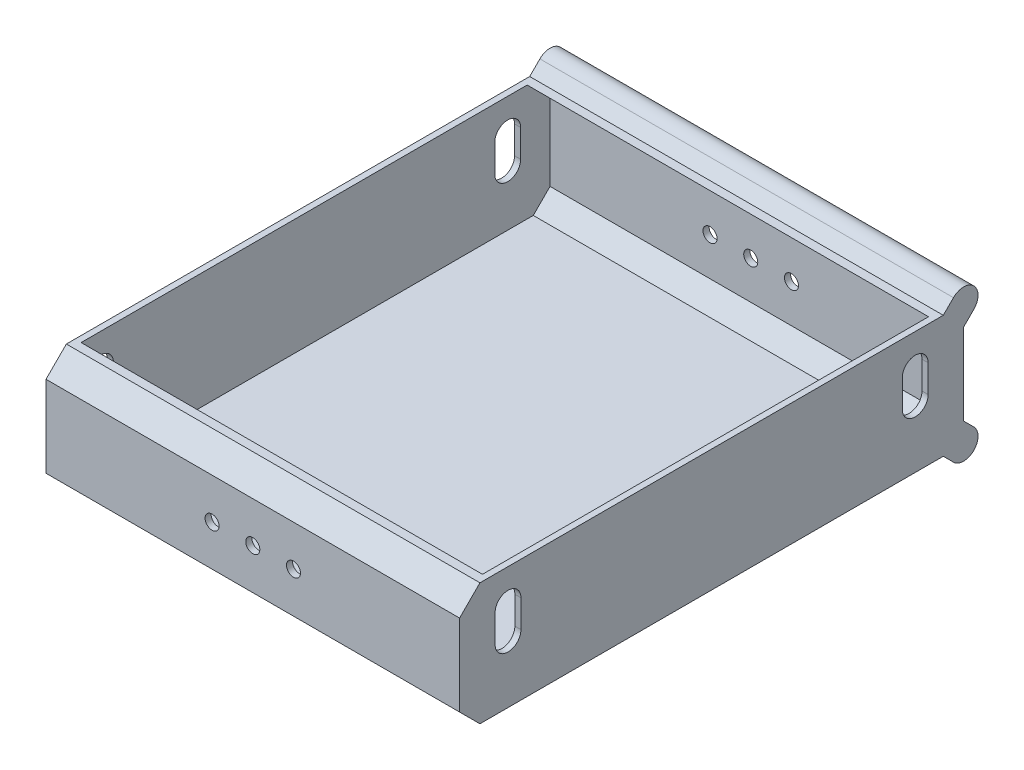
SolidWorks part; units mm, degrees
ref_plane "Front Plane" through (0, 0, 0) normal (0, 0, 1) x (1, 0, 0)
ref_plane "Top Plane" through (0, 0, 0) normal (0, 1, 0) x (1, 0, 0)
ref_plane "Right Plane" through (0, 0, 0) normal (1, 0, 0) x (0, 0, -1)
sketch "Sketch1" plane through (0, 0, 0) normal (0, 1, 0) x (1, 0, 0)
  line L1 (-101.6, 123.825) -> (101.6, 123.825)
  line L2 (-101.6, 123.825) -> (-101.6, -123.825)
  line L3 (-101.6, -123.825) -> (101.6, -123.825)
  line L4 (101.6, 123.825) -> (101.6, -123.825)
  line L5 (-101.6, 123.825) -> (101.6, -123.825) construction
  line L6 (-101.6, -123.825) -> (101.6, 123.825) construction
  point P0 (0, 0)
  dimension "D1" = 203.2
  dimension "D2" = 247.65
extrude "Boss-Extrude1" add sketch "Sketch1" along normal blind 60
chamfer "Chamfer1" distance 10 angle 45 4 edges at (0, 0, 123.825) (0, 60, 123.825) (0, 0, -123.825) (0, 60, -123.825)
shell "Shell3" thickness 3
sketch "Sketch2" plane through (-101.6, 0, 0) normal (-1, 0, 0) x (0, 0, 1)
  line L0 (-100.025, 43.55) -> (-100.025, 30) construction
  line L1 (-93.675, 43.55) -> (-93.675, 30)
  line L2 (-106.375, 43.55) -> (-106.375, 30)
  line L3 (-123.825, 50) -> (-123.825, 10) construction
  arc A0 (-93.675, 43.55) -> (-106.375, 43.55) centre (-100.025, 43.55) ccw
  arc A1 (-106.375, 30) -> (-93.675, 30) centre (-100.025, 30) ccw
  point P2 (-100.025, 36.775)
  point P12 (-123.825, 30)
  dimension "D1" = 12.7
  dimension "D2" = 13.55
  dimension "D3" = 23.8
extrude "Cut-Extrude1" cut sketch "Sketch2" against normal up to next
mirror "Mirror1" about plane through (0, 0, 0) normal (0, 0, 1) of "Cut-Extrude1" second plane through (0, 0, 0) second plane normal (1, 0, 0)
sketch "Sketch3" plane through (0, 0, -123.825) normal (0, 0, -1) x (-1, 0, 0)
  line L0 (-101.6, 30) -> (101.6, 30) construction
  line L1 (-101.6, 50) -> (-101.6, 10) construction
  line L2 (101.6, 50) -> (101.6, 10) construction
  circle A0 centre (0, 30) radius 3.45
  circle A1 centre (20, 30) radius 3.45
  circle A2 centre (-20, 30) radius 3.45
  point P16 (0, 30)
  dimension "D1" = 6.9
  dimension "D2" = 20
  dimension "D3" = 20
extrude "Cut-Extrude2" cut sketch "Sketch3" against normal up to next
mirror "Mirror2" about plane through (0, 0, 0) normal (0, 0, 1) of "Cut-Extrude2"
sketch "Sketch4" plane through (-101.6, 0, 0) normal (-1, 0, 0) x (0, 0, 1)
  line L0 (-113.825, 60) -> (-123.825, 50) construction
  line L2 (-123.825, 50) -> (-128.825, 55)
  line L3 (-113.825, 60) -> (-118.825, 65)
  line L4 (-123.825, 30) -> (123.825, 30) construction
  line L7 (-123.825, 10) -> (-113.825, 0)
  line L8 (-113.825, 0) -> (-118.825, -5)
  line L9 (-123.825, 50) -> (-123.825, 10) construction
  line L10 (-123.825, 50) -> (-113.825, 60)
  line L11 (-123.825, 10) -> (-128.825, 5)
  arc A0 (-118.825, 65) -> (-128.825, 55) centre (-123.825, 60) ccw
  arc A3 (-118.825, -5) -> (-128.825, 5) centre (-123.825, 0) cw
  point P20 (-123.825, 30)
extrude "Boss-Extrude2" add sketch "Sketch4" against normal up to surface (203.2 mm away) up to face at (101.6, 36.775, 100.025)
